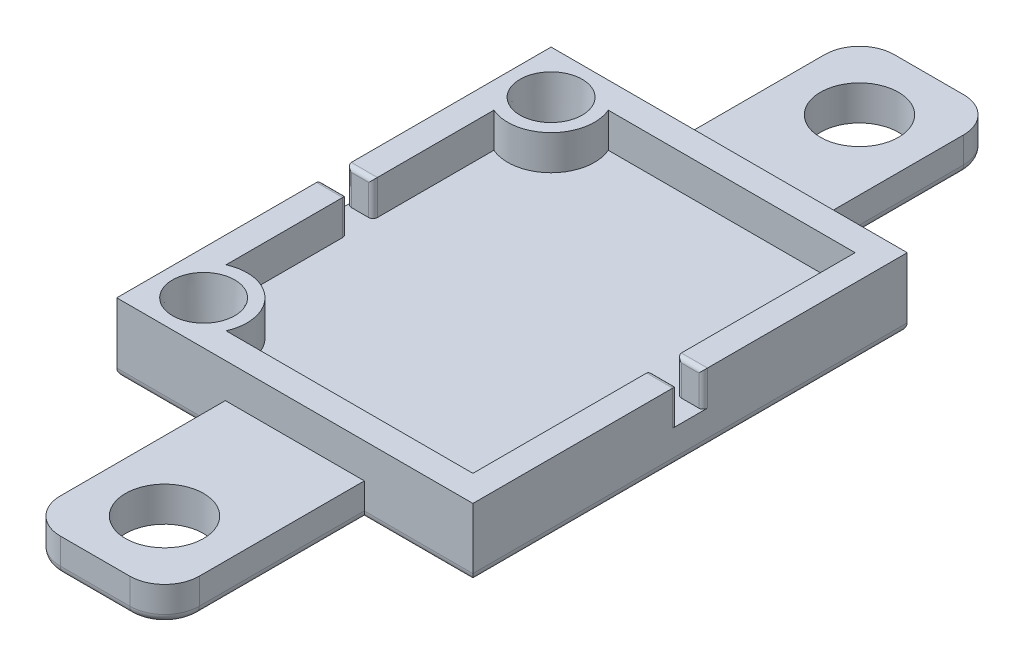
SolidWorks part; units mm, degrees
ref_plane "Front Plane" through (0, 0, 0) normal (0, 0, 1) x (1, 0, 0)
ref_plane "Top Plane" through (0, 0, 0) normal (0, 1, 0) x (1, 0, 0)
ref_plane "Right Plane" through (0, 0, 0) normal (1, 0, 0) x (0, 0, -1)
sketch "Sketch1" plane through (0, 0, 0) normal (0, 1, 0) x (1, 0, 0)
  line L0 (-15.2941, 0) -> (15.2941, 0) construction
  line L1 (-10.25, -12.5) -> (10.25, -12.5) construction
  line L2 (-10.25, -12.5) -> (-10.25, 12.5) construction
  line L3 (-10.25, 12.5) -> (10.25, 12.5) construction
  line L4 (10.25, -12.5) -> (10.25, 12.5) construction
  line L5 (-10.25, -12.5) -> (10.25, 12.5) construction
  line L6 (-10.25, 12.5) -> (10.25, -12.5) construction
  line L7 (0, 17.7941) -> (0, -15.2451) construction
  line L9 (4.2192, 0.7868) -> (5.9892, 0.7868) construction
  line L10 (4.2192, 0.7868) -> (4.2192, 8.9068) construction
  line L11 (4.2192, 8.9068) -> (5.9892, 8.9068) construction
  line L12 (5.9892, 0.7868) -> (5.9892, 8.9068) construction
  line L13 (4.2192, 0.7868) -> (5.9892, 8.9068) construction
  line L14 (4.2192, 8.9068) -> (5.9892, 0.7868) construction
  line L15 (4.2192, -9.3732) -> (5.9892, -9.3732) construction
  line L16 (4.2192, -9.3732) -> (4.2192, -1.2532) construction
  line L17 (4.2192, -1.2532) -> (5.9892, -1.2532) construction
  line L18 (5.9892, -9.3732) -> (5.9892, -1.2532) construction
  line L19 (4.2192, -9.3732) -> (5.9892, -1.2532) construction
  line L20 (4.2192, -1.2532) -> (5.9892, -9.3732) construction
  line L21 (-7.6426, 0.5788) -> (-5.8726, 0.5788) construction
  line L22 (-7.6426, 0.5788) -> (-7.6426, 6.1588) construction
  line L23 (-7.6426, 6.1588) -> (-5.8726, 6.1588) construction
  line L24 (-5.8726, 0.5788) -> (-5.8726, 6.1588) construction
  line L25 (-7.6426, 0.5788) -> (-5.8726, 6.1588) construction
  line L26 (-7.6426, 6.1588) -> (-5.8726, 0.5788) construction
  circle A0 centre (-7.75, 10) radius 1.1 construction
  circle A1 centre (-7.75, -10) radius 1.1 construction
  point P0 (0, 0)
  point P14 (5.1042, 4.8468)
  point P19 (5.1042, -5.3132)
  point P25 (-6.7576, 3.3688)
  point P32 (-1.7156, -11.0712)
  dimension "D5" = 2.2
  dimension "D1" = 25
  dimension "D2" = 20.5
  dimension "D3" = 2.5
  dimension "D4" = 2.5
  dimension "D6" = 8.12
  dimension "D7" = 1.77
  dimension "D8" = 7.6532
  dimension "D9" = 15.3542
  dimension "D10" = 17.8132
  dimension "D11" = 5.58
  dimension "D12" = 3.4924
  dimension "D13" = 9.1312
  dimension "D14" = 8.5344
  dimension "D15" = 23.5712
sketch "Sketch2" plane through (0, 0, 0) normal (0, 1, 0) x (1, 0, 0)
  line L0 (-15.2941, 0) -> (15.2941, 0) construction
  line L1 (-10.25, -12.5) -> (10.25, -12.5)
  line L2 (-10.25, -12.5) -> (-10.25, 12.5)
  line L3 (-10.25, 12.5) -> (10.25, 12.5)
  line L4 (10.25, -12.5) -> (10.25, 12.5)
  line L5 (-10.25, -12.5) -> (10.25, 12.5) construction
  line L6 (-10.25, 12.5) -> (10.25, -12.5) construction
  circle A0 centre (-7.75, 10) radius 1.15
  circle A1 centre (-7.75, -10) radius 1.15
  point P0 (0, 0)
  dimension "D1" = 2.3
extrude "Boss-Extrude1" add sketch "Sketch2" along normal blind 4
sketch "Sketch3" plane through (0, 4, 0) normal (0, 1, 0) x (1, 0, 0)
  line L0 (-15.2941, 0) -> (15.2941, 0) construction
  line L1 (-5.4587, 11) -> (8.75, 11)
  line L2 (-10.25, -12.5) -> (10.25, -12.5)
  line L3 (-10.25, -12.5) -> (-10.25, 12.5)
  line L4 (-10.25, 12.5) -> (10.25, 12.5)
  line L5 (10.25, -12.5) -> (10.25, 12.5)
  line L6 (-10.25, -12.5) -> (10.25, 12.5) construction
  line L7 (-10.25, 12.5) -> (10.25, -12.5) construction
  line L8 (8.75, -11) -> (8.75, 11)
  line L9 (-5.4587, -11) -> (8.75, -11)
  line L10 (-8.75, -7.7087) -> (-8.75, 7.7087)
  line L12 (-8.75, 11) -> (8.75, 11) construction
  line L13 (-8.75, -11) -> (8.75, -11) construction
  line L14 (-8.75, -11) -> (-8.75, 11) construction
  arc A0 (-8.75, 7.7087) -> (-5.4587, 11) centre (-7.75, 10) ccw
  arc A1 (-8.75, -7.7087) -> (-5.4587, -11) centre (-7.75, -10) cw
  point P9 (0, 0)
  dimension "D1" = 5
  dimension "D2" = 1.5
extrude "Cut-Extrude1" cut sketch "Sketch3" against normal blind 2 flip side to cut
sketch "Sketch4" plane through (0, 4, 0) normal (0, 1, 0) x (1, 0, 0)
  line L0 (-15.2941, 0) -> (15.2941, 0) construction
  circle A0 centre (-7.75, 10) radius 1.79
  circle A1 centre (-7.75, -10) radius 1.79
  dimension "D1" = 3.58
extrude "Cut-Extrude2" cut sketch "Sketch4" against normal blind 2.92
draft "Draft1" type of draft neutral plane draft angle 4 faces to draft 2 face at (-7.75, 1.08, 8.21) face at (-7.75, 1.08, -8.21) neutral plane through (0, 4, 0) neutral plane normal (0, 1, 0) parameters "D1"=4
sketch "Sketch5" plane through (0, 0, 0) normal (0, -1, 0) x (1, 0, 0)
  line L0 (-15.2941, 0) -> (15.2941, 0) construction
  line L1 (0, 15.2451) -> (0, -17.7941) construction
  line L7 (-10.25, 12.5) -> (10.25, 12.5) construction
  line L8 (-4, 24) -> (4, 24)
  line L13 (-4, 24) -> (-4, 12.5)
  line L14 (-4, 12.5) -> (4, 12.5)
  line L15 (4, 24) -> (4, 12.5)
  line L16 (-4, 24) -> (4, 12.5) construction
  line L17 (-4, 12.5) -> (4, 24) construction
  line L18 (-4, -24) -> (-4, -12.5)
  line L19 (-4, -12.5) -> (4, -12.5)
  line L20 (4, -24) -> (4, -12.5)
  line L21 (-4, -24) -> (4, -24)
  circle A2 centre (0, 20) radius 2.2479
  circle A3 centre (0, -20) radius 2.2479
  point P10 (0, 18.25)
  dimension "D1" = 4.4958
  dimension "D4" = 11.5
  dimension "D2" = 20
  dimension "D3" = 8
extrude "Boss-Extrude2" add sketch "Sketch5" against normal blind 2
fillet "Fillet1" radius 2 4 edges at (-4, 1, -24) (4, 1, -24) (4, 1, 24) (-4, 1, 24)
fillet "Fillet2" radius 0.5 16 edges at (-4, 0, 17.25) (-3.4142, 0, 23.4142) (0, 0, 24) (3.4142, 0, 23.4142) (4, 0, -17.25) (3.4142, 0, -23.4142) (0, 0, -24) (-3.4142, 0, -23.4142) (-7.125, 0, 12.5) (4, 0, 17.25) (7.125, 0, 12.5) (10.25, 0, 0) (7.125, 0, -12.5) (-4, 0, -17.25) (-7.125, 0, -12.5) (-10.25, 0, 0)
sketch "Sketch7" plane through (-10.25, 0, 0) normal (-1, 0, 0) x (0, 0, 1)
  line L0 (0, 13.2159) -> (0, -7.5904) construction
  line L1 (-12.5, 4) -> (12.5, 4) construction
  line L2 (-0.75, 2) -> (0.75, 2)
  line L3 (-0.75, 2) -> (-0.75, 4)
  line L4 (-0.75, 4) -> (0.75, 4)
  line L5 (0.75, 2) -> (0.75, 4)
  line L6 (-0.75, 2) -> (0.75, 4) construction
  line L7 (-0.75, 4) -> (0.75, 2) construction
  point P3 (0, 3)
  dimension "D1" = 1.5
  dimension "D2" = 2
extrude "Cut-Extrude4" cut sketch "Sketch7" against normal through all
fillet "Fillet3" radius 0.25 12 edges at (10.25, 3, 0.75) (9.5, 4, 0.75) (9.5, 4, -0.75) (8.75, 3, 0.75) (10.25, 3, -0.75) (8.75, 3, -0.75) (-8.75, 3, 0.75) (-9.5, 4, 0.75) (-10.25, 3, 0.75) (-9.5, 4, -0.75) (-10.25, 3, -0.75) (-8.75, 3, -0.75)
